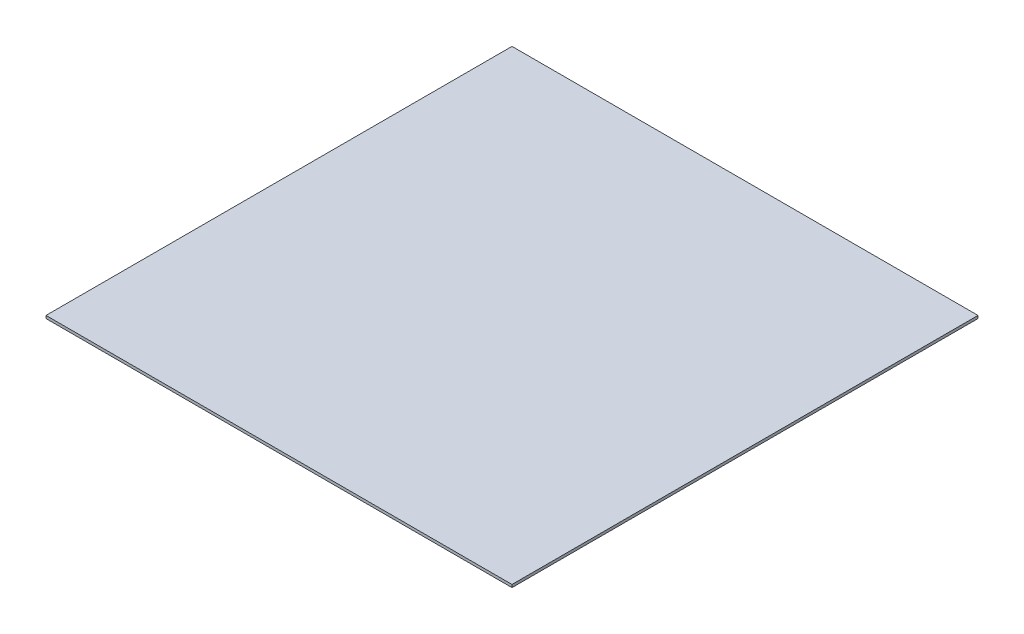
SolidWorks part; units mm, degrees
ref_plane "Front Plane" through (0, 0, 0) normal (0, 0, 1) x (1, 0, 0)
ref_plane "Top Plane" through (0, 0, 0) normal (0, 1, 0) x (1, 0, 0)
ref_plane "Right Plane" through (0, 0, 0) normal (1, 0, 0) x (0, 0, -1)
sketch "Sketch1" plane through (0, 0, 0) normal (0, 1, 0) x (1, 0, 0)
  line L1 (254, -254) -> (-254, -254)
  line L2 (254, -254) -> (254, 254)
  line L3 (254, 254) -> (-254, 254)
  line L4 (-254, -254) -> (-254, 254)
  line L5 (0, 254) -> (0, -254) construction
  line L6 (254, 0) -> (-254, 0) construction
  point P0 (0, 0)
  dimension "D1" = 508
  dimension "D2" = 508
extrude "Boss-Extrude1" add sketch "Sketch1" along normal blind 3
